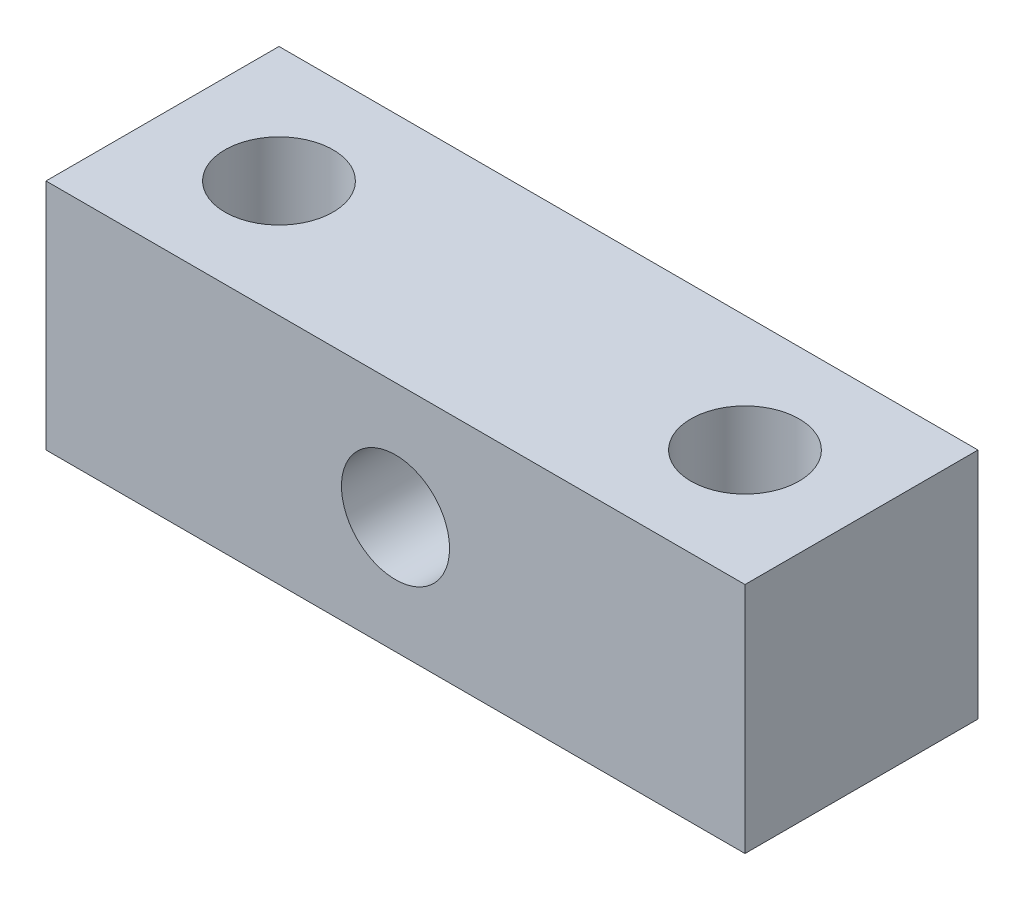
SolidWorks part; units mm, degrees
ref_plane "Front Plane" through (0, 0, 0) normal (0, 0, 1) x (1, 0, 0)
ref_plane "Top Plane" through (0, 0, 0) normal (0, 1, 0) x (1, 0, 0)
ref_plane "Right Plane" through (0, 0, 0) normal (1, 0, 0) x (0, 0, -1)
sketch "Sketch1" plane through (0, 0, 0) normal (0, 0, 1) x (1, 0, 0)
  line L0 (-9.525, 3.175) -> (9.525, -3.175) construction
  line L1 (-9.525, 3.175) -> (9.525, 3.175)
  line L2 (-9.525, 3.175) -> (-9.525, -3.175)
  line L3 (-9.525, -3.175) -> (9.525, -3.175)
  line L4 (9.525, 3.175) -> (9.525, -3.175)
  point P4 (0, 0)
  point P5 (-9.525, -2.4547)
  dimension "D1" = 19.05
  dimension "D2" = 6.35
extrude "Boss-Extrude1" add sketch "Sketch1" along normal blind 6.35
hole_wizard "#4 Clearance Hole1" positions "Sketch2" profile "Sketch3" hole size "#4" standard "ANSI Inch" end condition through all
sketch "Sketch2" plane through (0, 3.175, 0) normal (0, 1, 0) x (1, 0, 0)
  line L0 (0, 0) -> (0, -6.35) construction
  line L1 (9.525, 0) -> (-9.525, 0) construction
  line L2 (9.525, -6.35) -> (-9.525, -6.35) construction
  line L4 (-9.525, -6.35) -> (-9.525, 0) construction
  point P0 (-6.35, -3.175)
  point P12 (0, 0)
  point P13 (6.35, -3.175)
  point P14 (-5.9746, -2.8063)
  point P15 (0, 0)
  point P16 (0, -3.175)
  dimension "D1" = 3.175
sketch "Sketch3" plane through (-6.35, 3.175, 3.175) normal (1, 0, 0) x (0, 0, 1)
  line L0 (0, 0) -> (0, 6.35)
  line L1 (0, 6.35) -> (1.4732, 6.35)
  line L2 (1.4732, 6.35) -> (1.4732, 0)
  line L5 (1.4732, 0) -> (0, 0)
  line L11 (0, -6.35) -> (0, 107.95) construction
  dimension "Thru Hole Dia." = 2.9464
  dimension "Thru Hole Depth" = 6.35
hole_wizard "#4 Clearance Hole2" positions "Sketch4" profile "Sketch5" hole size "#4" standard "ANSI Inch" end condition through all
sketch "Sketch4" plane through (0, 0, 6.35) normal (0, 0, 1) x (1, 0, 0)
  line L0 (-9.525, 0) -> (9.525, 0) construction
  line L1 (-9.525, 3.175) -> (-9.525, -3.175) construction
  line L2 (9.525, -3.175) -> (9.525, 3.175) construction
  point P0 (0, 0)
  point P10 (0, 0)
  point P11 (0, 0)
sketch "Sketch5" plane through (0, 0, 6.35) normal (1, 0, 0) x (0, -1, 0)
  line L0 (0, 0) -> (0, 6.35)
  line L1 (0, 6.35) -> (1.4732, 6.35)
  line L2 (1.4732, 6.35) -> (1.4732, 0)
  line L5 (1.4732, 0) -> (0, 0)
  line L11 (0, -6.35) -> (0, 107.95) construction
  dimension "Thru Hole Dia." = 2.9464
  dimension "Thru Hole Depth" = 6.35
